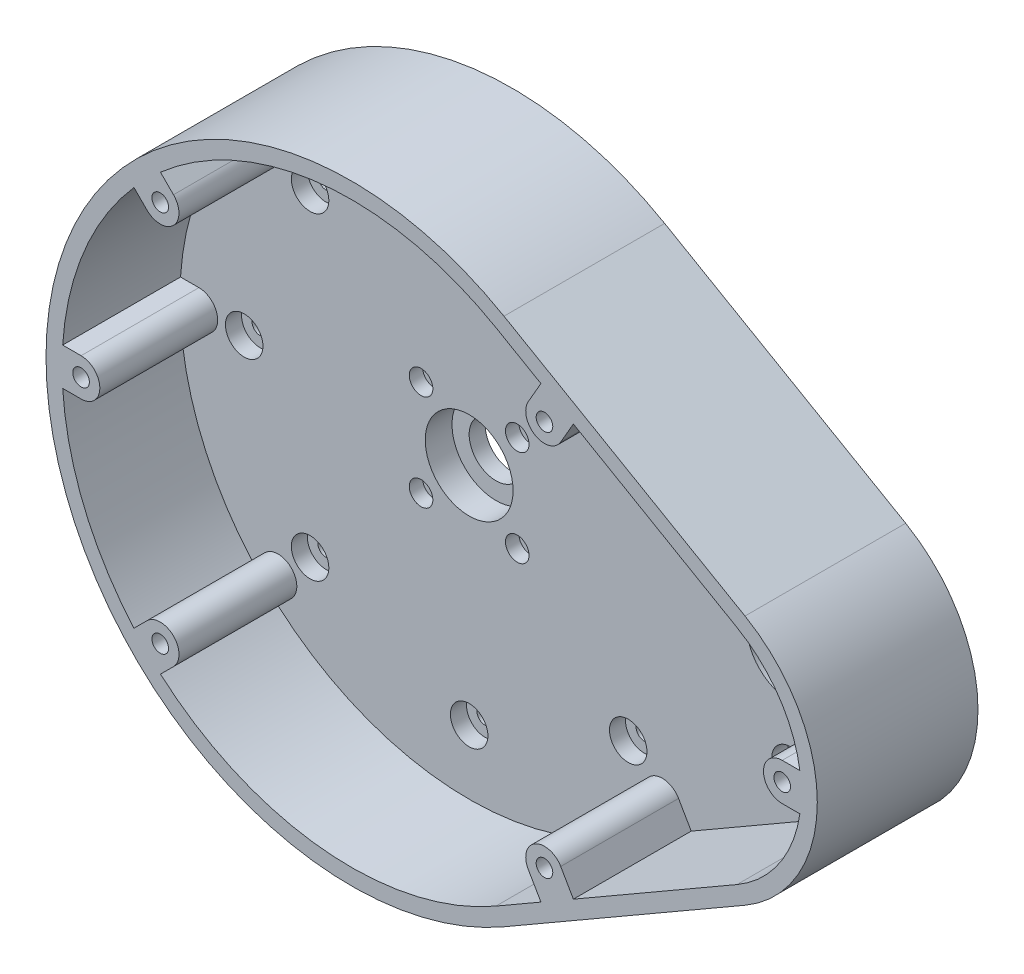
SolidWorks part; units mm, degrees
ref_plane "Front Plane" through (0, 0, 0) normal (0, 0, 1) x (1, 0, 0)
ref_plane "Top Plane" through (0, 0, 0) normal (0, 1, 0) x (1, 0, 0)
ref_plane "Right Plane" through (0, 0, 0) normal (1, 0, 0) x (0, 0, -1)
sketch "Sketch1" plane through (0, 0, 0) normal (0, 0, 1) x (1, 0, 0)
  line L0 (-30, 0) -> (30, 0) construction
  line L3 (-1.5, 49.3634) -> (43.5, 23.3827)
  line L4 (-1.5, -49.3634) -> (43.5, -23.3827)
  circle A0 centre (-30, 0) radius 57 construction
  circle A1 centre (30, 0) radius 27 construction
  circle A4 centre (-30, 0) radius 46.5 construction
  circle A5 centre (30, 0) radius 16.5 construction
  arc A6 (-1.5, 49.3634) -> (-1.5, -49.3634) centre (-30, 0) ccw
  arc A7 (43.5, 23.3827) -> (43.5, -23.3827) centre (30, 0) cw
  point P4 (0, 0)
extrude "Boss-Extrude1" add sketch "Sketch1" along normal blind 30 contours L4 A7 L3 A6
sketch "Sketch3" plane through (0, 0, 30) normal (0, 0, 1) x (1, 0, 0)
  line L3 (-3, -46.7654) -> (5.4002, -41.9155)
  line L4 (42, 20.7846) -> (11.4624, 38.4155)
  line L7 (-63.1987, -38.1484) -> (-65.6286, -40.5784)
  line L10 (-30, 0) -> (-65.6735, 35.6735) construction
  line L11 (-68.1484, 33.1987) -> (-63.1987, 38.1484) construction
  line L29 (-80.45, 3.5) -> (-83.8865, 3.5)
  line L30 (-80.45, -3.5) -> (-83.8865, -3.5)
  line L34 (-68.1484, 33.1987) -> (-70.5784, 35.6286)
  line L36 (-63.1987, 38.1484) -> (-65.6286, 40.5784)
  line L37 (-30, 0) -> (-65.6735, -35.6735) construction
  line L38 (30, 0) -> (50.45, 0.0259) construction
  line L45 (50.45, 3.5259) -> (53.7396, 3.5259)
  line L46 (50.45, -3.4741) -> (53.7472, -3.4741)
  line L49 (-63.1987, -38.1484) -> (-68.1484, -33.1987) construction
  line L50 (-68.1484, -33.1987) -> (-70.5784, -35.6286)
  line L54 (-80.45, 0) -> (-30, 0) construction
  line L57 (-30, 0) -> (6.0624, 36.0624) construction
  line L58 (3.0314, 37.8124) -> (9.0935, 34.3124) construction
  line L59 (9.0935, 34.3124) -> (11.4624, 38.4155)
  line L63 (3.0314, 37.8124) -> (5.4002, 41.9155)
  line L64 (5.4002, 41.9155) -> (-3, 46.7654)
  line L65 (-30, 0) -> (6.0624, -36.0624) construction
  line L66 (3.0314, -37.8124) -> (9.0935, -34.3124) construction
  line L67 (3.0314, -37.8124) -> (5.4002, -41.9155)
  line L68 (9.0935, -34.3124) -> (11.4624, -38.4155)
  line L69 (11.4624, -38.4155) -> (42, -20.7846)
  arc A12 (50.45, -3.4741) -> (50.45, 3.5259) centre (50.45, 0.0259) cw
  circle A13 centre (50.45, 0.0259) radius 1.55
  circle A41 centre (-80.45, 0) radius 1.55
  arc A42 (-80.45, 3.5) -> (-80.45, -3.5) centre (-80.45, 0) cw
  arc A61 (-3, 46.7654) -> (-65.6286, 40.5784) centre (-30, 0) ccw
  arc A62 (-83.8865, -3.5) -> (-70.5784, -35.6286) centre (-30, 0) ccw
  circle A64 centre (-65.6735, 35.6735) radius 1.55
  arc A65 (42, 20.7846) -> (53.7396, 3.5259) centre (30, 0) cw
  arc A66 (53.7472, -3.4741) -> (42, -20.7846) centre (30, 0) cw
  arc A67 (-68.1484, 33.1987) -> (-63.1987, 38.1484) centre (-65.6735, 35.6735) ccw
  arc A68 (-70.5784, 35.6286) -> (-83.8865, 3.5) centre (-30, 0) ccw
  circle A69 centre (-65.6735, -35.6735) radius 1.55
  arc A70 (-68.1484, -33.1987) -> (-63.1987, -38.1484) centre (-65.6735, -35.6735) cw
  arc A71 (-65.6286, -40.5784) -> (-3, -46.7654) centre (-30, 0) ccw
  circle A72 centre (6.0624, 36.0624) radius 1.55
  arc A73 (3.0314, 37.8124) -> (9.0935, 34.3124) centre (6.0624, 36.0624) ccw
  circle A74 centre (6.0624, -36.0624) radius 1.55
  arc A75 (3.0314, -37.8124) -> (9.0935, -34.3124) centre (6.0624, -36.0624) cw
  point P10 (-30, 0)
  point P20 (-30, 0)
  point P22 (-30, 0)
  point P30 (-65.6735, 35.6735)
  point P32 (-30, 0)
  point P35 (-30, 0)
  point P37 (-30, 0)
  point P39 (-30, 0)
  point P42 (-65.6735, -35.6735)
  point P48 (6.0624, 36.0624)
  point P51 (-30, 0)
  point P58 (6.0624, -36.0624)
  point P59 (-30, 0)
extrude "Cut-Extrude1" cut sketch "Sketch3" against normal blind 22
sketch "Sketch5" plane through (0, 0, 0) normal (0, 0, -1) x (-1, 0, 0)
  circle A13 centre (80.45, 0) radius 1.55
  circle A15 centre (-50.45, 0.0259) radius 1.55
  circle A20 centre (-6.0624, -36.0624) radius 1.55
  circle A21 centre (-6.0624, 36.0624) radius 1.55
  circle A22 centre (65.6735, 35.6735) radius 1.55
  circle A25 centre (65.6735, -35.6735) radius 1.55
extrude "Cut-Extrude2" cut sketch "Sketch5" against normal blind 30
sketch "Sketch6" plane through (0, 0, 0) normal (0, 0, -1) x (-1, 0, 0)
  circle A12 centre (-50.45, 0.0259) radius 3.5
  circle A15 centre (80.45, 0) radius 3.5
  circle A20 centre (65.6735, 35.6735) radius 3.5
  circle A21 centre (-6.0624, 36.0624) radius 3.5
  circle A22 centre (65.6735, -35.6735) radius 3.5
  circle A23 centre (-6.0624, -36.0624) radius 3.5
extrude "Cut-Extrude3" cut sketch "Sketch6" against normal blind 5
sketch "Sketch7" plane through (0, 0, 8) normal (0, 0, 1) x (1, 0, 0)
  line L0 (30, 0) -> (-30, 0) construction
  circle A4 centre (-30, 0) radius 8.2
  circle A9 centre (30, 0) radius 8.2
  point P5 (0, 0)
extrude "Cut-Extrude10" cut sketch "Sketch7" against normal blind 5
sketch "Sketch8" plane through (0, 0, 8) normal (0, 0, 1) x (1, 0, 0)
  line L0 (-30, 0) -> (-38.9803, 8.9803) construction
  circle A0 centre (-30, 0) radius 5
  circle A1 centre (-30, 0) radius 12.7 construction
  circle A2 centre (-38.9803, 8.9803) radius 1.05
  circle A3 centre (-21.0197, 8.9803) radius 1.05
  circle A4 centre (-21.0197, -8.9803) radius 1.05
  circle A5 centre (-38.9803, -8.9803) radius 1.05
  point P7 (-30, 0)
  point P10 (-30, 0)
  point P17 (-30, 0)
  dimension "D1" = 4
extrude "Cut-Extrude7" cut sketch "Sketch8" against normal blind 8
sketch "Sketch9" plane through (0, 0, 8) normal (0, 0, 1) x (1, 0, 0)
  circle A0 centre (-38.9803, 8.9803) radius 2.2
  circle A1 centre (-21.0197, 8.9803) radius 2.2
  circle A2 centre (-21.0197, -8.9803) radius 2.2
  circle A3 centre (-38.9803, -8.9803) radius 2.2
  point P12 (-30, 0)
  dimension "D1" = 4
extrude "Cut-Extrude8" cut sketch "Sketch9" against normal blind 2.5
sketch "Sketch10" plane through (0, 0, 30) normal (0, 0, 1) x (1, 0, 0)
  line L0 (-3.0003, 46.7655) -> (42, 20.7849)
  line L2 (-3.0003, -46.7655) -> (42, -20.7849)
  line L3 (-4, 45.0333) -> (41, 19.0526)
  line L4 (-4, -45.0333) -> (41, -19.0526)
  circle A0 centre (-30, 0) radius 54 construction
  circle A1 centre (30, 0) radius 24.0003 construction
  arc A2 (-3.0003, 46.7655) -> (-3.0003, -46.7655) centre (-30, 0) ccw
  arc A3 (42, 20.7849) -> (42, -20.7849) centre (30, 0) cw
  circle A4 centre (-30, 0) radius 52 construction
  circle A5 centre (30, 0) radius 22 construction
  arc A6 (41, 19.0526) -> (41, -19.0526) centre (30, 0) cw
  arc A7 (-4, 45.0333) -> (-4, -45.0333) centre (-30, 0) ccw
sketch "Sketch11" plane through (0, 0, 8) normal (0, 0, 1) x (1, 0, 0)
  line L0 (-30, 0) -> (-0.3015, 29.6985) construction
  line L1 (30, -19) -> (30, 19) construction
  line L2 (30, 0) -> (42, 0) construction
  line L3 (30, 0) -> (42, 0) construction
  circle A0 centre (-30, 0) radius 42 construction
  circle A1 centre (-0.3015, 29.6985) radius 1.55
  circle A2 centre (-30, 42) radius 1.55
  circle A3 centre (-59.6985, 29.6985) radius 1.55
  circle A4 centre (-72, 0) radius 1.55
  circle A5 centre (-59.6985, -29.6985) radius 1.55
  circle A6 centre (-30, -42) radius 1.55
  circle A7 centre (-0.3015, -29.6985) radius 1.55
  circle A8 centre (30, 19) radius 1.55
  circle A9 centre (30, -19) radius 1.55
  circle A10 centre (42, 0) radius 1.55
  point P19 (-30, 0)
  point P24 (30, 0)
  point P29 (30, 0)
  dimension "D1" = 7
extrude "Cut-Extrude11" cut sketch "Sketch11" against normal blind 8
sketch "Sketch12" plane through (0, 0, 8) normal (0, 0, 1) x (1, 0, 0)
  line L0 (-0.3015, 29.6985) -> (-30, 0) construction
  circle A0 centre (-0.3015, 29.6985) radius 3.5
  circle A1 centre (-30, 42) radius 3.5
  circle A2 centre (-59.6985, 29.6985) radius 3.5
  circle A3 centre (-72, 0) radius 3.5
  circle A4 centre (-59.6985, -29.6985) radius 3.5
  circle A5 centre (-30, -42) radius 3.5
  circle A6 centre (-0.3015, -29.6985) radius 3.5
  circle A7 centre (30, 19) radius 3.5
  circle A8 centre (42, 0) radius 3.5
  circle A9 centre (30, -19) radius 3.5
  point P20 (-30, 0)
  dimension "D1" = 7
extrude "Cut-Extrude12" cut sketch "Sketch12" against normal blind 3
